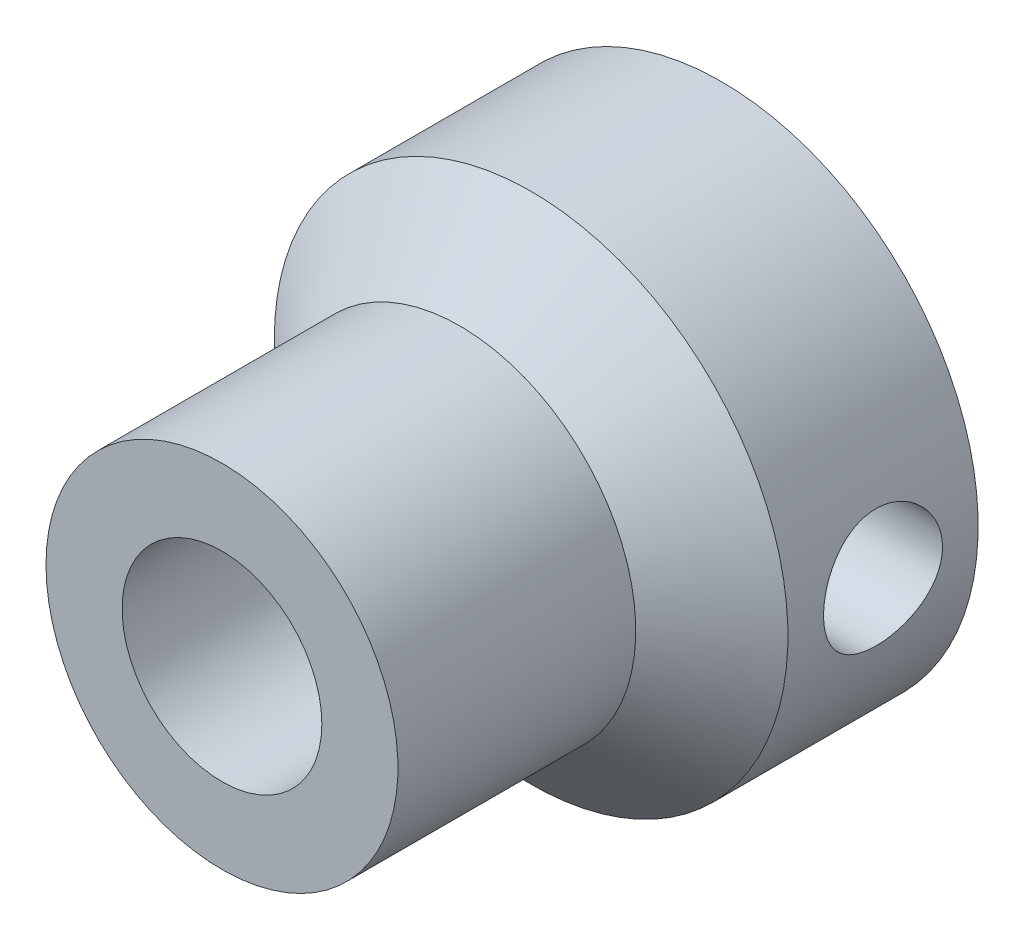
SolidWorks part; units mm, degrees
ref_plane "Top" through (0, 0, 0) normal (0, 0, 1) x (1, 0, 0)
ref_plane "Front" through (0, 0, 0) normal (0, 1, 0) x (1, 0, 0)
ref_plane "Right" through (0, 0, 0) normal (1, 0, 0) x (0, 0, -1)
ref_plane "Base Tangent Plane" through (5.4, 0, 0) normal (1, 0, 0) x (0, 0, -1)
sketch "Body Sketch" plane through (0, 0, 0) normal (0, 1, 0) x (-1, 0, 0)
  line L1 (1, 10.5) -> (3.7, 10.5)
  line L2 (3.7, 10.5) -> (3.7, 5.5)
  line L3 (3.7, 5.5) -> (5.4, 4)
  line L4 (5.4, 4) -> (5.4, 0)
  line L5 (5.4, 0) -> (2.5, 0)
  line L8 (0, 0) -> (0, 10.5) construction
  line L9 (1, 10.5) -> (1, 5)
  line L10 (1, 5) -> (2.5, 5)
  line L11 (2.5, 5) -> (2.5, 0)
  dimension "D1" = 4
  dimension "D6" = 5
  dimension "D2" = 10.5
  dimension "D4" = 5.4
  dimension "D3" = 3.7
  dimension "D5" = 2.5
  dimension "D7" = 1
  dimension "D8" = 5
revolve "Body Revolve" add sketch "Body Sketch" angle 360 about L8
hole_wizard "Connector M5x0.8 Tapped Hole" positions "Connector Position Sketch" profile "Sketch5" tap size "M5x0.8" standard "ANSI Metric" end condition through all
sketch "Connector Position Sketch" plane through (0, 0, 10.5) normal (0, 0, 1) x (1, 0, 0)
  point P0 (0, 0)
cosmetic thread "Connector Hole Thread"
sketch "Sketch5" plane through (0, 0, 10.5) normal (1, 0, 0) x (0, -1, 0)
  line L0 (0, 0) -> (0, 10.5)
  line L1 (0, 10.5) -> (2.1, 10.5)
  line L2 (2.1, 10.5) -> (2.1, 0)
  line L5 (2.1, 0) -> (0, 0)
  line L11 (0, -6.35) -> (0, 107.95) construction
  dimension "Thru Tap Drill Dia." = 4.2
  dimension "Thru Tap Drill Depth" = 10.5
hole_wizard "Set Screw 1 M3x0.5 Tapped Hole" positions "Set Screw Position Sketch" profile "Set Screw Profile Sketch" tap size "M3x0.5" standard "ANSI Metric"
sketch3d "Set Screw Position Sketch"
  point P0 (5.4, 0, 2)
  dimension "D1" = 2
sketch "Set Screw Profile Sketch" plane through (5.4, 0, 2) normal (0, 1, 0) x (0, 0, -1)
  line L0 (0, 0) -> (0, 2.9)
  line L1 (0, 2.9) -> (1.25, 2.9)
  line L2 (1.25, 2.9) -> (1.25, 0)
  line L5 (1.25, 0) -> (0, 0)
  line L11 (0, -6.35) -> (0, 107.95) construction
  dimension "Thru Tap Drill Dia." = 2.5
  dimension "Thru Tap Drill Depth" = 2.9
cosmetic thread "Set Screw 1 Hole Thread"
pattern_circular "Set Screw 2 Pattern" count 2 over 360 about axis through (0, 0, 2) along (1, 0, 0) of "Set Screw 1 M3x0.5 Tapped Hole"
cosmetic thread "Hole Thread3"
equation "\"Base Diameter\"= 10.8"
equation "\"D4@Body Sketch\"=\"Base Diameter\"/2"
equation "\"D1@Base Tangent Plane\"=\"Base Diameter\"/2"
